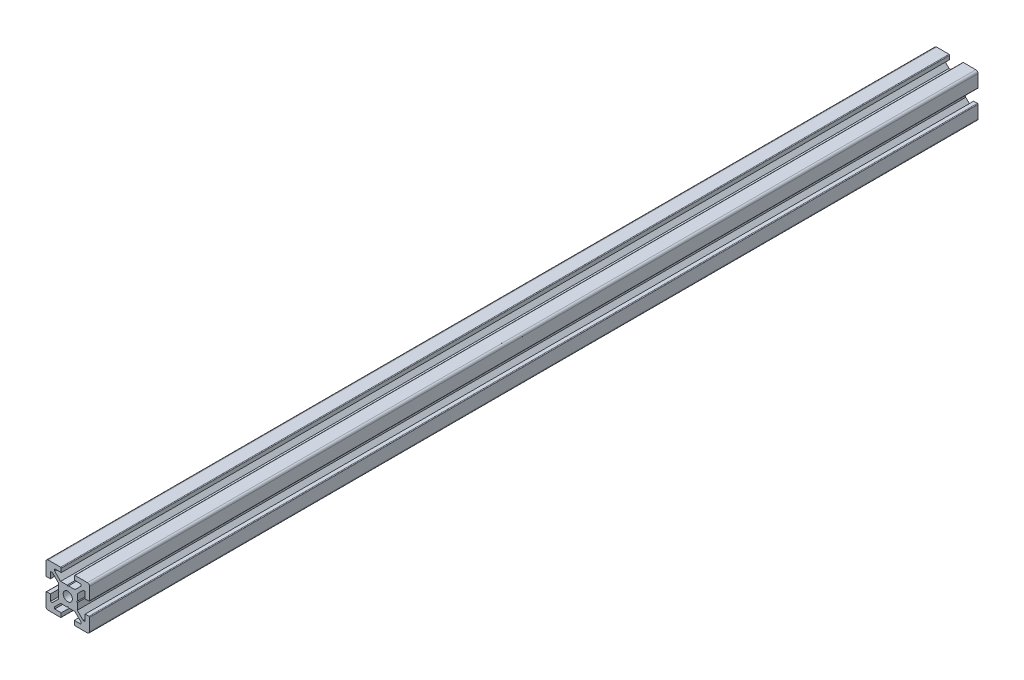
SolidWorks part; units mm, degrees
ref_plane "Front Plane" through (0, 0, 0) normal (0, 0, 1) x (1, 0, 0)
ref_plane "Top Plane" through (0, 0, 0) normal (0, 1, 0) x (1, 0, 0)
ref_plane "Right Plane" through (0, 0, 0) normal (1, 0, 0) x (0, 0, -1)
sketch "Sketch1" plane through (0, 0, 0) normal (0, 0, 1) x (1, 0, 0)
  line L0 (0, 0) -> (0, 4.3607) construction
  line L1 (-10, 10) -> (10, 10) construction
  line L2 (-10, 10) -> (-10, -10) construction
  line L3 (-10, -10) -> (10, -10) construction
  line L4 (10, 10) -> (10, -10) construction
  line L5 (-10, 10) -> (10, -10) construction
  line L6 (-10, -10) -> (10, 10) construction
  line L7 (0, 4.3607) -> (3.3, 4.3607) construction
  line L8 (3.3, 4.3607) -> (6, 7.0607)
  line L9 (6, 7.0607) -> (6, 8)
  line L10 (6, 8) -> (3, 8)
  line L11 (3, 8) -> (3, 9.7)
  line L12 (3.3, 10) -> (9, 10)
  line L13 (0, 4.0607) -> (0.3, 4.3607)
  line L14 (0.3, 4.3607) -> (3.3, 4.3607)
  line L15 (10, 3.3) -> (10, 9)
  line L16 (8, 3) -> (9.7, 3)
  line L17 (8, 6) -> (8, 3)
  line L18 (7.0607, 6) -> (8, 6)
  line L19 (4.3607, 3.3) -> (7.0607, 6)
  line L20 (4.3607, 0.3) -> (4.3607, 3.3)
  line L21 (4.0607, 0) -> (4.3607, 0.3)
  line L22 (4.0607, 0) -> (4.3607, -0.3)
  line L23 (4.3607, -0.3) -> (4.3607, -3.3)
  line L24 (4.3607, -3.3) -> (7.0607, -6)
  line L25 (7.0607, -6) -> (8, -6)
  line L26 (8, -6) -> (8, -3)
  line L27 (8, -3) -> (9.7, -3)
  line L28 (10, -3.3) -> (10, -9)
  line L29 (3.3, -10) -> (9, -10)
  line L30 (3, -8) -> (3, -9.7)
  line L31 (6, -8) -> (3, -8)
  line L32 (6, -7.0607) -> (6, -8)
  line L33 (3.3, -4.3607) -> (6, -7.0607)
  line L34 (0.3, -4.3607) -> (3.3, -4.3607)
  line L35 (0, -4.0607) -> (0.3, -4.3607)
  line L36 (0, -4.0607) -> (-0.3, -4.3607)
  line L37 (-0.3, -4.3607) -> (-3.3, -4.3607)
  line L38 (-3.3, -4.3607) -> (-6, -7.0607)
  line L39 (-6, -7.0607) -> (-6, -8)
  line L40 (-6, -8) -> (-3, -8)
  line L41 (-3, -8) -> (-3, -9.7)
  line L42 (-3.3, -10) -> (-9, -10)
  line L43 (-10, -3.3) -> (-10, -9)
  line L44 (-8, -3) -> (-9.7, -3)
  line L45 (-8, -6) -> (-8, -3)
  line L46 (-7.0607, -6) -> (-8, -6)
  line L47 (-4.3607, -3.3) -> (-7.0607, -6)
  line L48 (-4.3607, -0.3) -> (-4.3607, -3.3)
  line L49 (-4.0607, 0) -> (-4.3607, -0.3)
  line L50 (-4.0607, 0) -> (-4.3607, 0.3)
  line L51 (-4.3607, 0.3) -> (-4.3607, 3.3)
  line L52 (-4.3607, 3.3) -> (-7.0607, 6)
  line L53 (-7.0607, 6) -> (-8, 6)
  line L54 (-8, 6) -> (-8, 3)
  line L55 (-8, 3) -> (-9.7, 3)
  line L56 (-10, 3.3) -> (-10, 9)
  line L57 (-3.3, 10) -> (-9, 10)
  line L58 (-3, 8) -> (-3, 9.7)
  line L59 (-6, 8) -> (-3, 8)
  line L60 (-6, 7.0607) -> (-6, 8)
  line L61 (-3.3, 4.3607) -> (-6, 7.0607)
  line L62 (-0.3, 4.3607) -> (-3.3, 4.3607)
  line L63 (0, 4.0607) -> (-0.3, 4.3607)
  arc A0 (3, 9.7) -> (3.3, 10) centre (3.3, 9.7) cw
  arc A1 (9, 10) -> (10, 9) centre (9, 9) cw
  arc A2 (9.7, 3) -> (10, 3.3) centre (9.7, 3.3) ccw
  arc A3 (9.7, -3) -> (10, -3.3) centre (9.7, -3.3) cw
  arc A4 (10, -9) -> (9, -10) centre (9, -9) cw
  arc A5 (3, -9.7) -> (3.3, -10) centre (3.3, -9.7) ccw
  arc A6 (-3, -9.7) -> (-3.3, -10) centre (-3.3, -9.7) cw
  arc A7 (-9, -10) -> (-10, -9) centre (-9, -9) cw
  arc A8 (-9.7, -3) -> (-10, -3.3) centre (-9.7, -3.3) ccw
  arc A9 (-9.7, 3) -> (-10, 3.3) centre (-9.7, 3.3) cw
  arc A10 (-10, 9) -> (-9, 10) centre (-9, 9) cw
  arc A11 (-3, 9.7) -> (-3.3, 10) centre (-3.3, 9.7) ccw
  circle A12 centre (0, 0) radius 2.1
  point P0 (0, 0)
  point P95 (0, 0)
  dimension "D4" = 1
  dimension "D5" = 0.3
  dimension "D12" = 4.2
  dimension "D1" = 20
  dimension "D2" = 20
  dimension "D3" = 2
  dimension "D6" = 0.75
  dimension "D7" = 3
  dimension "D8" = 0.9393
  dimension "D9" = 3
  dimension "D10" = 0.3
  dimension "D11" = 4
extrude "Boss-Extrude1" add sketch "Sketch1" along normal up to vertex (267.7514 mm away)
